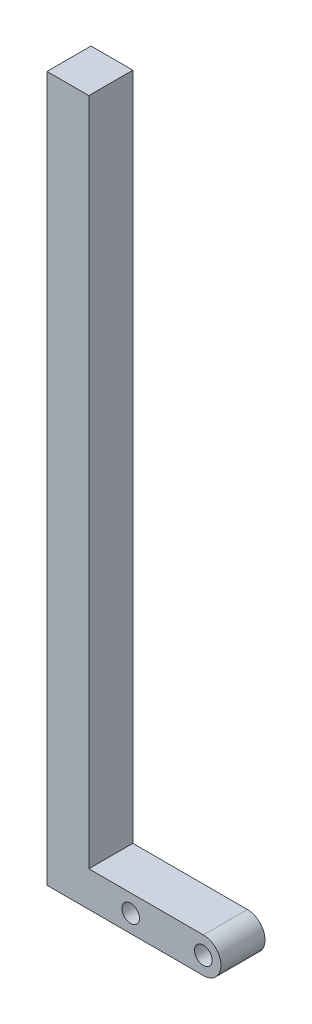
SolidWorks part; units mm, degrees
ref_plane "前视基准面" through (0, 0, 0) normal (0, 0, 1) x (1, 0, 0)
ref_plane "上视基准面" through (0, 0, 0) normal (0, 1, 0) x (1, 0, 0)
ref_plane "右视基准面" through (0, 0, 0) normal (1, 0, 0) x (0, 0, -1)
other "Configuration Table"
sketch "草图1" plane through (0, 0, 0) normal (0, 0, 1) x (1, 0, 0)
  line L0 (0, 0) -> (8.25, 0) construction
  line L1 (0, 2) -> (8.25, 2)
  line L2 (8.25, -2) -> (-0.5, -2)
  line L3 (0, 0) -> (-9.5, 0) construction
  line L4 (-0.5, -2) -> (-9.5, -2)
  line L5 (-9.5, -2) -> (-9.5, 78)
  line L6 (-9.5, 78) -> (-4.75, 78)
  line L7 (-4.75, 78) -> (-4.75, 2)
  line L8 (-4.75, 2) -> (0, 2)
  arc A1 (8.25, -2) -> (8.25, 2) centre (8.25, 0) ccw
  circle A2 centre (0, 0) radius 1
  circle A3 centre (8.25, 0) radius 1
  dimension "D1" = 8.25
  dimension "D3" = 4
  dimension "D6" = 2
  dimension "D7" = 2
  dimension "D2" = 8.25
  dimension "D4" = 9.5
  dimension "D5" = 4.75
  dimension "D8" = 80
extrude "凸台-拉伸1" add sketch "草图1" along normal blind 5
